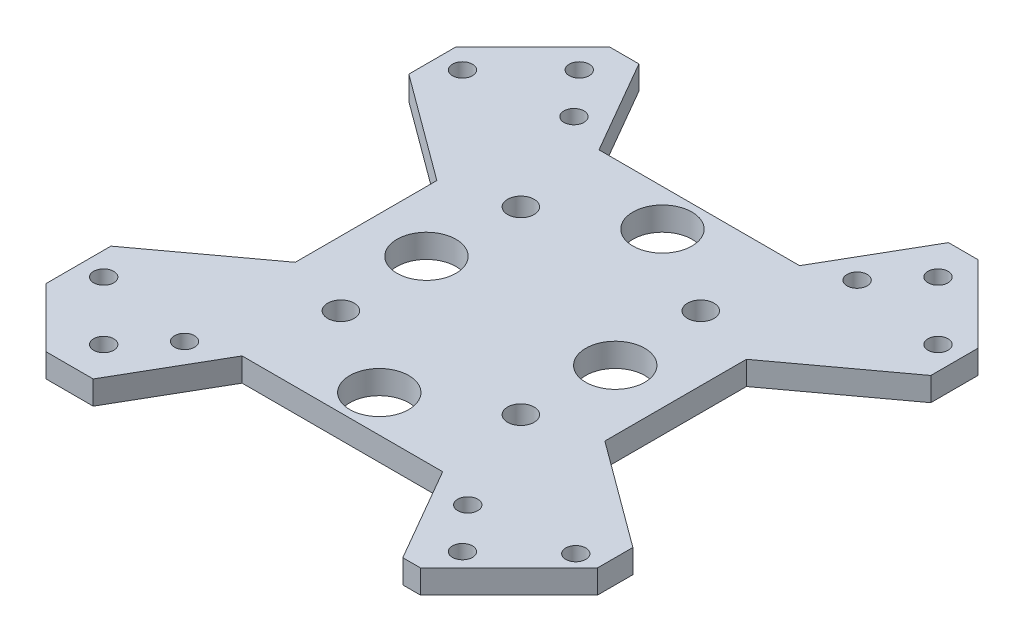
SolidWorks part; units mm, degrees
ref_plane "前视基准面" through (0, 0, 0) normal (0, 0, 1) x (1, 0, 0)
ref_plane "上视基准面" through (0, 0, 0) normal (0, 1, 0) x (1, 0, 0)
ref_plane "右视基准面" through (0, 0, 0) normal (1, 0, 0) x (0, 0, -1)
other "Configuration Table"
sketch "草图1" plane through (0, 0, 0) normal (0, 1, 0) x (1, 0, 0)
  line L8 (-40.3051, 30.4056) -> (-30.4056, 40.3051) construction
  line L9 (0, 0) -> (75.4458, 0) construction
  line L10 (0, 0) -> (0, 38.6741) construction
  line L21 (44.2385, 33.25) -> (44.2385, 25.25)
  line L22 (-44.2385, 33.25) -> (-44.2385, 25.25)
  line L23 (-34.2385, -46.25) -> (-26.2385, -46.25)
  line L24 (-31.2385, 46.25) -> (-26.2385, 46.25)
  line L25 (-44.2385, 33.25) -> (-31.2385, 46.25)
  line L26 (31.2385, 46.25) -> (44.2385, 33.25)
  line L27 (29.2385, -46.25) -> (44.2385, -31.25)
  line L28 (-44.2385, -36.25) -> (-34.2385, -46.25)
  line L30 (-26.2385, 12) -> (-26.2385, -12)
  line L32 (-44.2385, -25.25) -> (-44.2385, -36.25)
  line L33 (-44.2385, 25.25) -> (-26.2385, 12)
  line L34 (-44.2385, -25.25) -> (-26.2385, -12)
  line L35 (44.2385, -25.25) -> (26.2385, -12)
  line L36 (26.2385, 12) -> (26.2385, -12)
  line L37 (44.2385, 25.25) -> (26.2385, 12)
  line L38 (44.2385, -25.25) -> (44.2385, -31.25)
  line L39 (-26.2385, 46.25) -> (-17, 30.2485)
  line L40 (-17, 30.2485) -> (17, 30.2485)
  line L41 (26.2385, 46.25) -> (17, 30.2485)
  line L42 (26.2385, 46.25) -> (31.2385, 46.25)
  line L43 (26.2385, -46.25) -> (17, -30.2485)
  line L44 (-17, -30.2485) -> (17, -30.2485)
  line L45 (-26.2385, -46.25) -> (-17, -30.2485)
  line L46 (26.2385, -46.25) -> (29.2385, -46.25)
  circle A0 centre (-15.25, -15.25) radius 2.25
  circle A1 centre (-15.25, 15.25) radius 2.25
  circle A2 centre (15.25, -15.25) radius 2.25
  circle A3 centre (15.25, 15.25) radius 2.25
  circle A4 centre (-24, -33) radius 1.7
  circle A9 centre (-16, 0) radius 5
  circle A10 centre (0, 24) radius 5
  circle A13 centre (-30.4056, -40.3051) radius 1.7
  circle A14 centre (-30.4056, 40.3051) radius 1.7
  circle A15 centre (-40.3051, 30.4056) radius 1.7
  circle A16 centre (30.4056, -40.3051) radius 1.7
  circle A17 centre (40.3051, -31) radius 1.6949
  circle A18 centre (40.3051, 30.4056) radius 1.6949
  circle A19 centre (30.4056, 40.3051) radius 1.7
  circle A20 centre (-40.3051, -30.4056) radius 1.7
  circle A21 centre (24, -33) radius 1.7
  circle A22 centre (24, 33) radius 1.7
  circle A23 centre (-24, 33) radius 1.7
  circle A24 centre (16, 0) radius 5
  circle A25 centre (0, -24) radius 5
  point P1 (-44.2385, -46.25)
  point P7 (-44.2385, 46.25)
  point P57 (44.2385, 46.25)
  point P58 (44.2385, -46.25)
  point P61 (-26.2385, 0)
  point P70 (0, 30.2485)
  dimension "D3" = 4.5
  dimension "D4" = 4.5
  dimension "D14" = 3.4
  dimension "D21" = 10
  dimension "D22" = 10
  dimension "D2" = 46.25
  dimension "D5" = 44.2385
  dimension "D6" = 60
  dimension "D7" = 18
  dimension "D9" = 24
  dimension "D10" = 16
  dimension "D11" = 40.3051
  dimension "D12" = 24
  dimension "D13" = 33
  dimension "D17" = 8
  dimension "D18" = 12
  dimension "D19" = 5
  dimension "D20" = 17
extrude "凸台-拉伸1" add sketch "草图1" along normal blind 4
